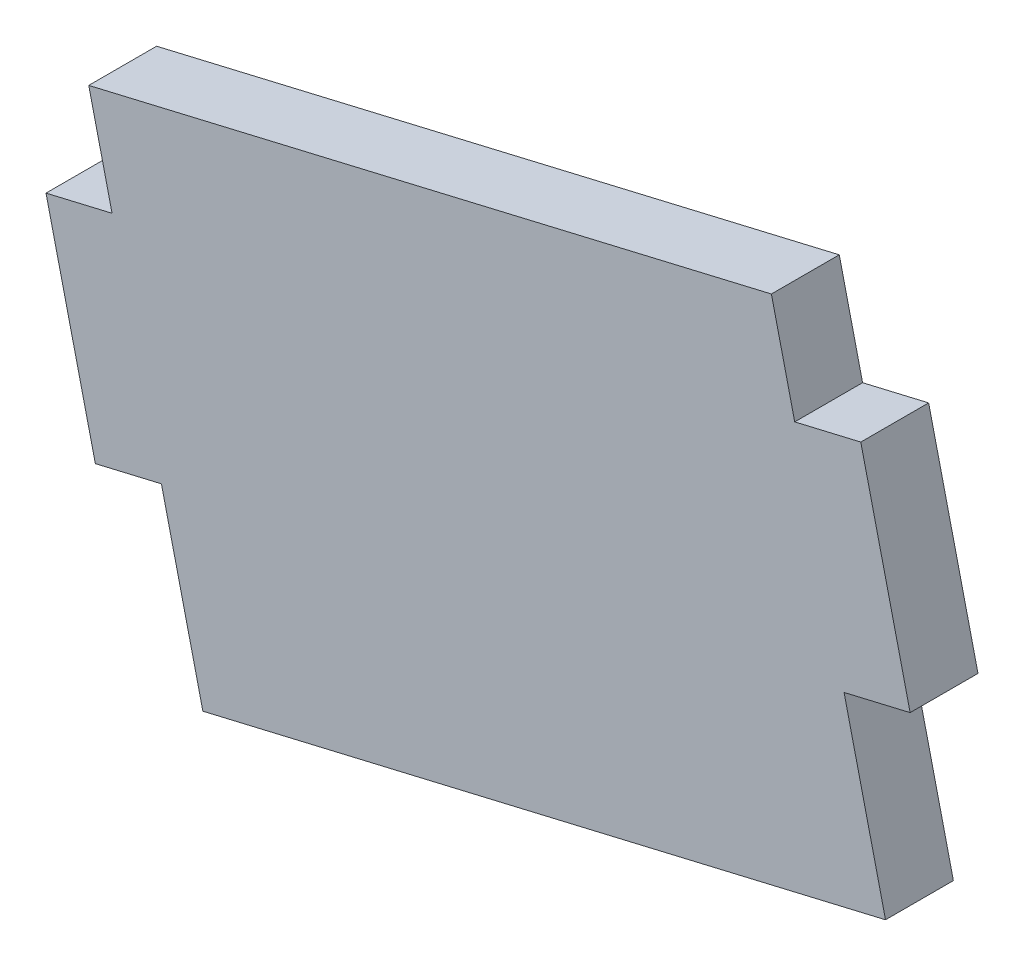
SolidWorks part; units mm, degrees
ref_plane "Front" through (0, 0, 0) normal (0, 0, 1) x (1, 0, 0)
ref_plane "Top" through (0, 0, 0) normal (0, 1, 0) x (1, 0, 0)
ref_plane "Right" through (0, 0, 0) normal (1, 0, 0) x (0, 0, -1)
sketch "Sketch1" plane through (0, 0, 0) normal (0, 0, 1) x (1, 0, 0)
  line L0 (643.0403, 392.2065) -> (642.0093, 396.5868)
  line L1 (616.8788, 368.0502) -> (647.0543, 375.1525)
  line L2 (642.0093, 396.5868) -> (611.8339, 389.4844)
  line L3 (612.8649, 385.1041) -> (611.8339, 389.4844)
  line L4 (616.8788, 368.0502) -> (615.046, 375.8374)
  line L5 (609.9447, 384.4168) -> (612.8649, 385.1041)
  line L6 (612.1258, 375.15) -> (615.046, 375.8374)
  line L7 (612.1258, 375.15) -> (609.9447, 384.4168)
  line L8 (648.1416, 383.627) -> (645.9605, 392.8938)
  line L9 (645.2214, 382.9397) -> (648.1416, 383.627)
  line L10 (647.0543, 375.1525) -> (645.2214, 382.9397)
  line L11 (643.0403, 392.2065) -> (645.9605, 392.8938)
  dimension "D1" = 9.52
  dimension "D2" = 9.52
  dimension "D3" = 8
  dimension "D4" = 4.5
  dimension "D5" = 90
  dimension "D6" = 90
  dimension "D7" = 90
  dimension "D8" = 90
  dimension "D9" = 90
  dimension "D10" = 3
  dimension "D11" = 90
extrude "Base-Extrude" add sketch "Sketch1" along normal blind 3
